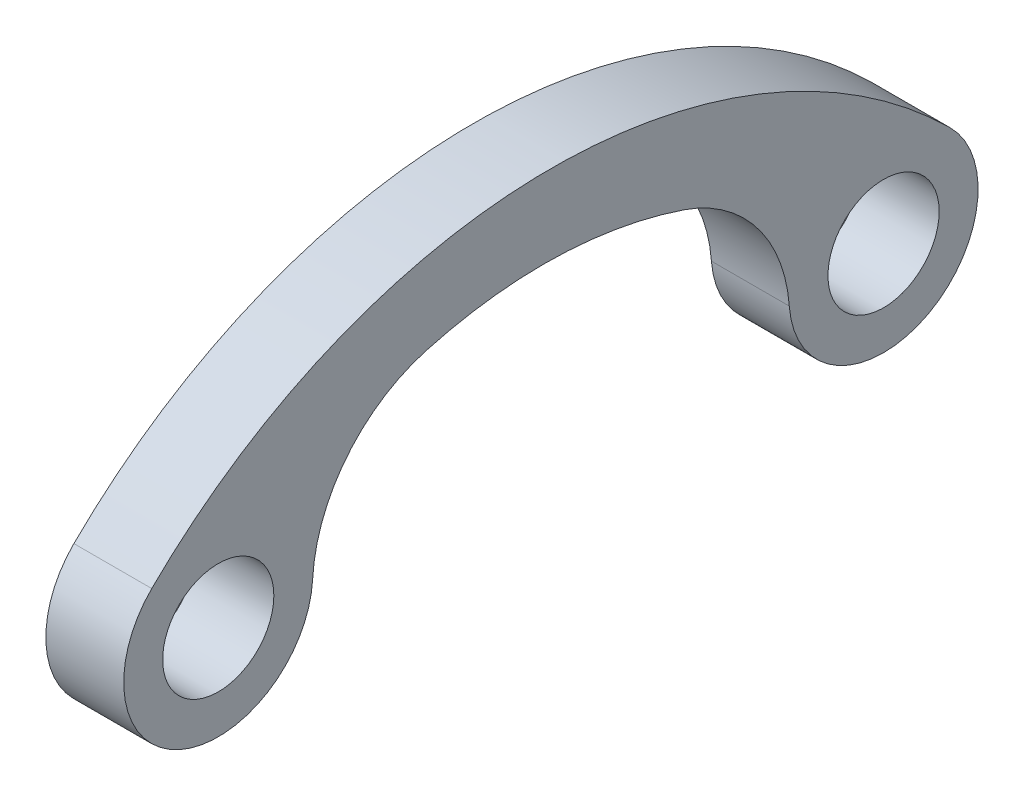
SolidWorks part; units mm, degrees
ref_plane "Front Plane" through (0, 0, 0) normal (0, 0, 1) x (1, 0, 0)
ref_plane "Top Plane" through (0, 0, 0) normal (0, 1, 0) x (1, 0, 0)
ref_plane "Right Plane" through (0, 0, 0) normal (1, 0, 0) x (0, 0, -1)
sketch "Sketch1" plane through (0, 0, 0) normal (1, 0, 0) x (0, 0, -1)
  line L0 (0, 0) -> (-36.65, 0) construction
  line L1 (-39.15, 0) -> (-42.72, 0) construction
  line L3 (-42.72, 0) -> (-21.36, 12.3322) construction
  line L4 (-21.36, 12.3322) -> (-21.36, 14.8322) construction
  line L5 (-21.36, 12.3322) -> (-21.36, 9.8322) construction
  line L6 (-5.2568, 3.035) -> (-21.36, 12.3322) construction
  circle A0 centre (0, 0) radius 3.57
  arc A1 (-1.9739, -5.7401) -> (4.2702, 4.314) centre (0, 0) ccw construction
  circle A2 centre (-42.72, 0) radius 3.57
  arc A3 (-46.9902, 4.314) -> (-40.7461, -5.7401) centre (-42.72, 0) ccw construction
  arc A6 (4.2702, 4.314) -> (-46.9902, 4.314) centre (-21.36, -21.5789) ccw
  arc A7 (-29.3762, 8.7321) -> (-36.6594, -0.3385) centre (-26.675, -0.8961) ccw
  arc A8 (-6.0534, -0.448) -> (4.2702, 4.314) centre (0, 0) ccw
  arc A9 (-46.9902, 4.314) -> (-36.6594, -0.3385) centre (-42.72, 0) ccw
  arc A10 (-12.8053, 8.2812) -> (-29.3762, 8.7321) centre (-21.8178, -18.2093) ccw
  arc A11 (-12.8053, 8.2812) -> (-6.0534, -0.448) centre (-16.0262, -1.1859) cw
  dimension "D1" = 7.14
  dimension "D2" = 2.5
  dimension "D4" = 7.14
  dimension "D5" = 2.5
  dimension "D7" = 10
  dimension "D8" = 2.5
  dimension "D3" = 42.72
  dimension "D6" = 21.36
  dimension "D9" = 2.5
extrude "Boss-Extrude1" add sketch "Sketch1" along normal blind 5
